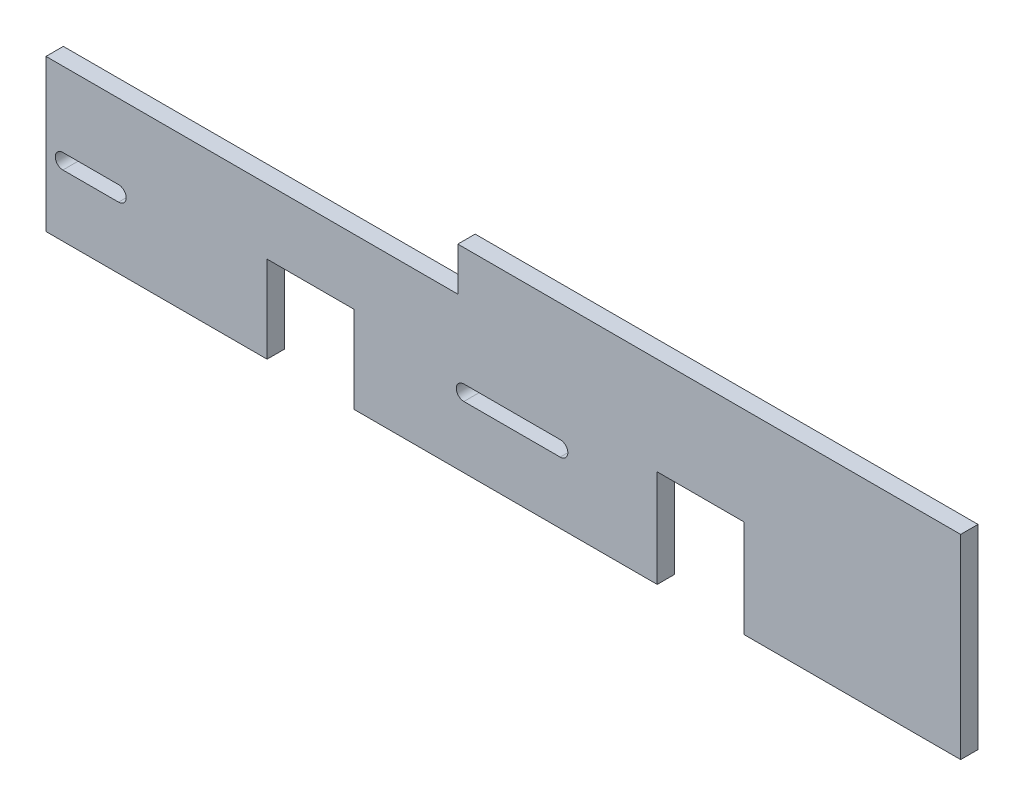
SolidWorks part; units mm, degrees
ref_plane "Front Plane" through (0, 0, 0) normal (0, 0, 1) x (1, 0, 0)
ref_plane "Top Plane" through (0, 0, 0) normal (0, 1, 0) x (1, 0, 0)
ref_plane "Right Plane" through (0, 0, 0) normal (1, 0, 0) x (0, 0, -1)
sketch "Sketch1" plane through (0, 0, 0) normal (0, 0, 1) x (1, 0, 0)
  line L1 (-105.5, -22.5) -> (105.5, -22.5)
  line L2 (-105.5, -22.5) -> (-105.5, 22.5)
  line L3 (-105.5, 22.5) -> (105.5, 22.5)
  line L4 (105.5, -22.5) -> (105.5, 22.5)
  line L5 (-105.5, -22.5) -> (105.5, 22.5) construction
  line L6 (-105.5, 22.5) -> (105.5, -22.5) construction
  point P0 (0, 0)
  dimension "D1" = 211
  dimension "D2" = 45
extrude "Boss-Extrude1" add sketch "Sketch1" along normal blind 4
sketch "Sketch2" plane through (0, 0, 4) normal (0, 0, 1) x (1, 0, 0)
  line L1 (-105.5, 22.5) -> (-10.5, 22.5)
  line L2 (-105.5, 22.5) -> (-105.5, 12.5)
  line L3 (-105.5, 12.5) -> (-10.5, 12.5)
  line L4 (-10.5, 22.5) -> (-10.5, 12.5)
  dimension "D1" = 95
  dimension "D2" = 10
extrude "Cut-Extrude1" cut sketch "Sketch2" against normal up to next
sketch "Sketch3" plane through (0, 0, 4) normal (0, 0, 1) x (1, 0, 0)
  line L0 (0, -22.5) -> (0, -10.5) construction
  line L1 (-105.5, -22.5) -> (105.5, -22.5) construction
  line L2 (-105.5, -10.5) -> (-44.5, -10.5) construction
  line L3 (-105.5, 12.5) -> (-105.5, -22.5) construction
  line L4 (-44.5, -10.5) -> (45.5, -10.5) construction
  line L5 (45.5, -10.5) -> (45.5, 0) construction
  line L6 (45.5, 0) -> (55.5, 0) construction
  line L7 (55.5, 0) -> (55.5, -22.5) construction
  line L8 (-105.5, -22.5) -> (105.5, -22.5) construction
  line L9 (45.5, 0) -> (35.5, 0) construction
  line L10 (35.5, 0) -> (35.5, -22.5) construction
  line L11 (55.5, -22.5) -> (55.5, 0)
  line L12 (55.5, 0) -> (35.5, 0)
  line L13 (35.5, 0) -> (35.5, -22.5)
  line L14 (35.5, -22.5) -> (55.5, -22.5)
  circle A0 centre (-44.5, -10.5) radius 4.5
  circle A1 centre (45.5, -10.5) radius 4.5
  dimension "D1" = 9
  dimension "D2" = 9
  dimension "D3" = 12
  dimension "D4" = 61
  dimension "D5" = 90
  dimension "D6" = 10
  dimension "D7" = 10
extrude "Cut-Extrude2" cut sketch "Sketch3" against normal up to next
sketch "Sketch4" plane through (0, 0, 0) normal (0, 0, -1) x (-1, 0, 0)
  line L0 (44.5, -10.5) -> (44.5, -22.5) construction
  line L1 (105.5, -22.5) -> (-35.5, -22.5) construction
  line L2 (44.5, -22.5) -> (34.5, -22.5)
  line L3 (34.5, -22.5) -> (34.5, -2.5)
  line L4 (34.5, -2.5) -> (54.5, -2.5)
  line L5 (54.5, -2.5) -> (54.5, -22.5)
  line L6 (54.5, -22.5) -> (44.5, -22.5)
  dimension "D1" = 20
  dimension "D2" = 10
  dimension "D3" = 10
extrude "Cut-Extrude3" cut sketch "Sketch4" against normal up to next (4 mm away)
sketch "Sketch5" plane through (0, 0, 0) normal (0, 0, -1) x (-1, 0, 0)
  line L9 (101.6015, -4.75) -> (88.7542, -4.75)
  line L10 (101.6015, -8.25) -> (88.7542, -8.25)
  arc A1 (88.7542, -8.25) -> (88.7542, -4.75) centre (88.7542, -6.5) cw
  arc A2 (101.6015, -4.75) -> (101.6015, -8.25) centre (101.6015, -6.5) cw
extrude "Cut-Extrude4" cut sketch "Sketch5" against normal up to next (4 mm away)
sketch "Sketch7" plane through (0, 0, 0) normal (0, 0, -1) x (-1, 0, 0)
  circle A0 centre (-45.5, -10.5) radius 5.7719
extrude "Cut-Extrude6" cut sketch "Sketch7" against normal through all
sketch "Sketch8" plane through (0, 0, 0) normal (0, 0, -1) x (-1, 0, 0)
  line L0 (-13.1255, -8.25) -> (9.1006, -8.25)
  line L1 (-3.7928, -4.75) -> (9.1006, -4.75)
  line L5 (-3.7928, -4.75) -> (-13.1255, -4.75)
  line L6 (34.5, -22.5) -> (-35.5, -22.5) construction
  arc A1 (-13.1255, -4.75) -> (-13.1255, -8.25) centre (-13.1255, -6.5) ccw
  arc A2 (9.1006, -8.25) -> (9.1006, -4.75) centre (9.1006, -6.5) ccw
  dimension "D1" = 14.25
extrude "Cut-Extrude7" cut sketch "Sketch8" against normal up to next
